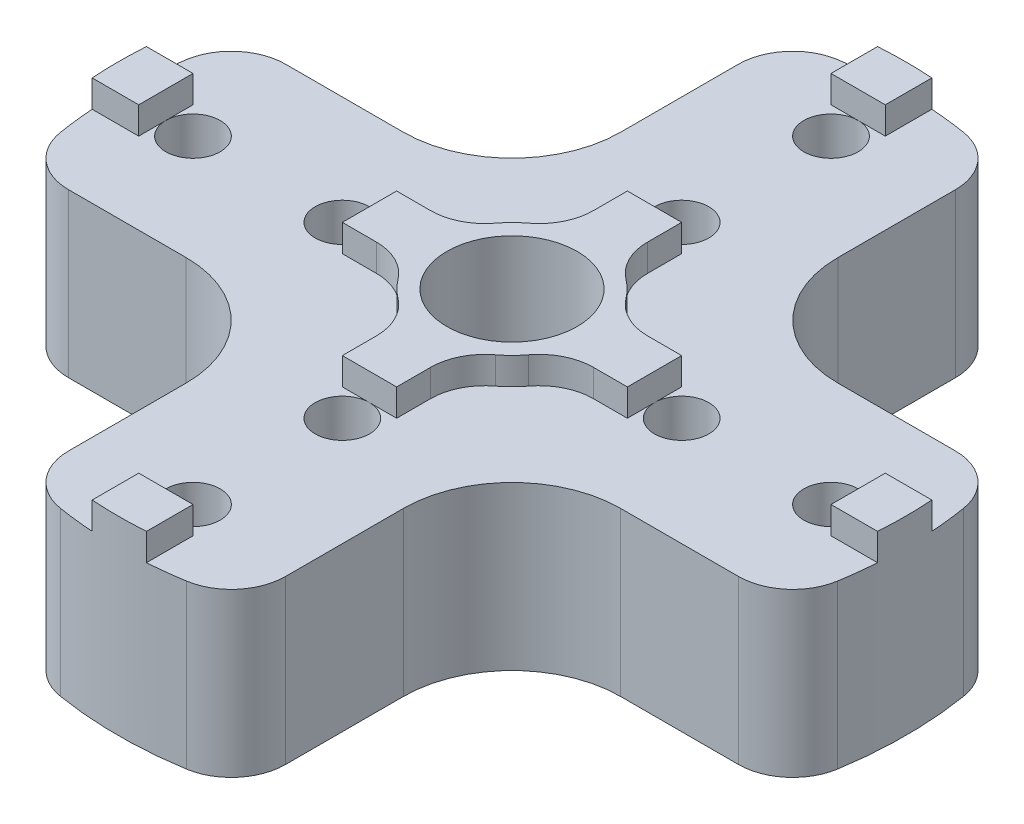
SolidWorks part; units mm, degrees
material "6061-T6 (SS)"
ref_plane "Front Plane" through (0, 0, 0) normal (0, 0, 1) x (1, 0, 0)
ref_plane "Top Plane" through (0, 0, 0) normal (0, 1, 0) x (1, 0, 0)
ref_plane "Right Plane" through (0, 0, 0) normal (1, 0, 0) x (0, 0, -1)
sketch "Sketch3" plane through (0, 0, 0) normal (0, 1, 0) x (1, 0, 0)
  line L0 (-2, -6.9687) -> (-2, -2)
  line L1 (-2, -2) -> (-6.9687, -2)
  line L2 (0, 0) -> (-7.25, 0) construction
  line L3 (0, 0) -> (0, -7.25) construction
  line L4 (0, 0) -> (-6.364, -6.364) construction
  line L5 (-6.9687, 2) -> (-2, 2)
  line L6 (-2, 2) -> (-2, 6.9687)
  line L7 (2, 6.9687) -> (2, 2)
  line L8 (2, 2) -> (6.9687, 2)
  line L9 (6.9687, -2) -> (2, -2)
  line L10 (2, -2) -> (2, -6.9687)
  arc A1 (-7.25, 0) -> (-6.9687, -2) centre (0, 0) ccw
  arc A2 (-2, -6.9687) -> (0, -7.25) centre (0, 0) ccw
  arc A3 (-6.9687, 2) -> (-7.25, 0) centre (0, 0) ccw
  arc A4 (0, 7.25) -> (-2, 6.9687) centre (0, 0) ccw
  arc A5 (2, 6.9687) -> (0, 7.25) centre (0, 0) ccw
  arc A6 (7.25, 0) -> (6.9687, 2) centre (0, 0) ccw
  arc A7 (6.9687, -2) -> (7.25, 0) centre (0, 0) ccw
  arc A8 (0, -7.25) -> (2, -6.9687) centre (0, 0) ccw
  point P29 (0, 0)
  dimension "D4" = 7.25
  dimension "D1" = 45
  dimension "D2" = 4
  dimension "D3" = 4
extrude "Boss-Extrude1" add sketch "Sketch3" along normal blind 2.5 and the other way blind 0.5
sketch "Sketch4" plane through (0, 2.5, 0) normal (0, 1, 0) x (-1, 0, 0)
  line L0 (0, 0) -> (0, 7.25) construction
  line L1 (-2, 4.5) -> (2, 4.5) construction
  line L3 (2, 2) -> (2, 6.9687) construction
  line L4 (-0.5, 5.875) -> (-0.5, 7.2327)
  line L5 (0.5, 5.875) -> (0.5, 7.2327)
  line L6 (0.5, 3.125) -> (0.5, 0.5)
  line L7 (-0.5, 3.125) -> (-0.5, 0.5)
  line L8 (0, 0) -> (6.364, 6.364) construction
  line L9 (0, 0) -> (-6.364, 6.364) construction
  line L10 (5.875, 0.5) -> (7.2327, 0.5)
  line L11 (5.875, -0.5) -> (7.2327, -0.5)
  line L12 (0.5, -5.875) -> (0.5, -7.2327)
  line L13 (-0.5, -5.875) -> (-0.5, -7.2327)
  line L14 (-5.875, -0.5) -> (-7.2327, -0.5)
  line L15 (-5.875, 0.5) -> (-7.2327, 0.5)
  line L16 (3.125, 0.5) -> (0.5, 0.5)
  line L17 (3.125, -0.5) -> (0.5, -0.5)
  line L18 (0.5, -3.125) -> (0.5, -0.5)
  line L19 (-0.5, -3.125) -> (-0.5, -0.5)
  line L20 (-3.125, -0.5) -> (-0.5, -0.5)
  line L21 (-3.125, 0.5) -> (-0.5, 0.5)
  line L22 (-2, 6.9687) -> (-2, 2) construction
  arc A0 (2, 6.9687) -> (-2, 6.9687) centre (0, 0) ccw construction
  arc A1 (-0.5, 5.875) -> (0.5, 5.875) centre (0, 5.875) ccw
  arc A2 (7.2327, -0.5) -> (7.2327, 0.5) centre (0, 0) ccw
  arc A4 (-0.5, 3.125) -> (0.5, 3.125) centre (0, 3.125) cw
  arc A5 (0.5, 7.2327) -> (-0.5, 7.2327) centre (0, 0) ccw
  arc A7 (5.875, 0.5) -> (5.875, -0.5) centre (5.875, 0) ccw
  arc A8 (-0.5, -7.2327) -> (0.5, -7.2327) centre (0, 0) ccw
  arc A9 (0.5, -5.875) -> (-0.5, -5.875) centre (0, -5.875) ccw
  arc A10 (-7.2327, 0.5) -> (-7.2327, -0.5) centre (0, 0) ccw
  arc A11 (-5.875, -0.5) -> (-5.875, 0.5) centre (-5.875, 0) ccw
  arc A12 (3.125, 0.5) -> (3.125, -0.5) centre (3.125, 0) cw
  arc A13 (0.5, -3.125) -> (-0.5, -3.125) centre (0, -3.125) cw
  arc A14 (-3.125, -0.5) -> (-3.125, 0.5) centre (-3.125, 0) cw
  point P47 (0, 0)
  point P63 (0, 0)
  point P70 (0, 0)
  dimension "D3" = 4
  dimension "D4" = 1
  dimension "D1" = 4.5
  dimension "D2" = 1.375
  dimension "D5" = 0
  dimension "D6" = 45
  dimension "D7" = 45
extrude "Boss-Extrude2" add sketch "Sketch4" along normal blind 0.5
sketch "Sketch5" plane through (0, 3, 0) normal (0, 1, 0) x (-1, 0, 0)
  circle A0 centre (0, 5.875) radius 0.5
  circle A1 centre (0, 3.125) radius 0.5
  arc A2 (0.5, 3.125) -> (-0.5, 3.125) centre (0, 3.125) ccw construction
  arc A3 (-0.5, 5.875) -> (0.5, 5.875) centre (0, 5.875) ccw construction
  circle A4 centre (5.875, 0) radius 0.5
  circle A5 centre (3.125, 0) radius 0.5
  circle A6 centre (0, -5.875) radius 0.5
  circle A7 centre (0, -3.125) radius 0.5
  circle A8 centre (-5.875, 0) radius 0.5
  circle A9 centre (-3.125, 0) radius 0.5
  point P27 (0, 0)
fillet "Fillet1" radius 1 8 edges at (2, 1, 6.9687) (6.9687, 1, 2) (-2, 1, 6.9687) (-6.9687, 1, 2) (6.9687, 1, -2) (2, 1, -6.9687) (-2, 1, -6.9687) (-6.9687, 1, -2)
extrude "Cut-Extrude1" cut sketch "Sketch5" against normal blind 3
sketch "Sketch10" plane through (0, 3, 0) normal (0, 1, 0) x (1, 0, 0)
  line L0 (-0.5, -5.875) -> (-0.5, -7.2327) construction
  line L1 (-0.5, -6.375) -> (0.5, -6.375)
  line L2 (-0.5, -6.375) -> (-0.5, -2.625)
  line L3 (-0.5, -2.625) -> (0.5, -2.625)
  line L4 (0.5, -6.375) -> (0.5, -2.625)
  line L5 (0.5, -7.2327) -> (0.5, -5.875) construction
  line L6 (-6.375, 0.5) -> (-2.625, 0.5)
  line L7 (-6.375, 0.5) -> (-6.375, -0.5)
  line L8 (-6.375, -0.5) -> (-2.625, -0.5)
  line L9 (-2.625, 0.5) -> (-2.625, -0.5)
  line L10 (0.5, 6.375) -> (0.5, 2.625)
  line L11 (0.5, 6.375) -> (-0.5, 6.375)
  line L12 (-0.5, 6.375) -> (-0.5, 2.625)
  line L13 (0.5, 2.625) -> (-0.5, 2.625)
  line L14 (6.375, -0.5) -> (2.625, -0.5)
  line L15 (6.375, -0.5) -> (6.375, 0.5)
  line L16 (6.375, 0.5) -> (2.625, 0.5)
  line L17 (2.625, -0.5) -> (2.625, 0.5)
  arc A0 (-0.5, -5.875) -> (0.5, -5.875) centre (0, -5.875) ccw construction
  arc A1 (0.5, -3.125) -> (-0.5, -3.125) centre (0, -3.125) ccw construction
  point P29 (0, 0)
  dimension "D1" = 4
extrude "Cut-Extrude2" cut sketch "Sketch10" against normal up to surface (0.5 mm away) up to face at (0, 2.5, 0)
sketch "Sketch17" plane through (0, 2.5, 0) normal (0, 1, 0) x (1, 0, 0)
  circle A0 centre (0, 0) radius 1.5
  dimension "D1" = 3
extrude "Boss-Extrude3" add sketch "Sketch17" along normal blind 0.5
hole_wizard "CSK for M2 Flat Head Machine Screw1" positions "Sketch15" profile "Sketch14" countersink size "M2" standard "ANSI Metric"
sketch "Sketch15" plane through (0, -0.5, 0) normal (0, -1, 0) x (-1, 0, 0)
  point P0 (0, 0)
sketch "Sketch14" plane through (0, -0.5, 0) normal (1, 0, 0) x (0, 0, -1)
  line L0 (0, 0) -> (0, 6.721)
  line L1 (0, 6.721) -> (1.2, 6)
  line L2 (1.2, 6) -> (1.2, 1)
  line L3 (1.2, 1) -> (2.2, 0)
  line L5 (2.2, 0) -> (0, 0)
  line L6 (-1.2, 1) -> (-2.2, 0) construction
  line L10 (0, 6.721) -> (-1.2, 6) construction
  line L11 (0, -6.35) -> (0, 107.95) construction
  dimension "Hole Dia." = 2.4
  dimension "Hole Depth" = 6
  dimension "Near C'Sink Dia." = 4.4
  dimension "Near C'Sink Angle" = 90
  dimension "Drill Angle" = 118
fillet "Fillet2" radius 2 4 edges at (2, 1, 2) (2, 1, -2) (-2, 1, -2) (-2, 1, 2)
fillet "Fillet3" radius 1 8 edges at (-1.4142, 2.75, -0.5) (-0.5, 2.75, -1.4142) (0.5, 2.75, -1.4142) (1.4142, 2.75, -0.5) (1.4142, 2.75, 0.5) (0.5, 2.75, 1.4142) (-0.5, 2.75, 1.4142) (-1.4142, 2.75, 0.5)
